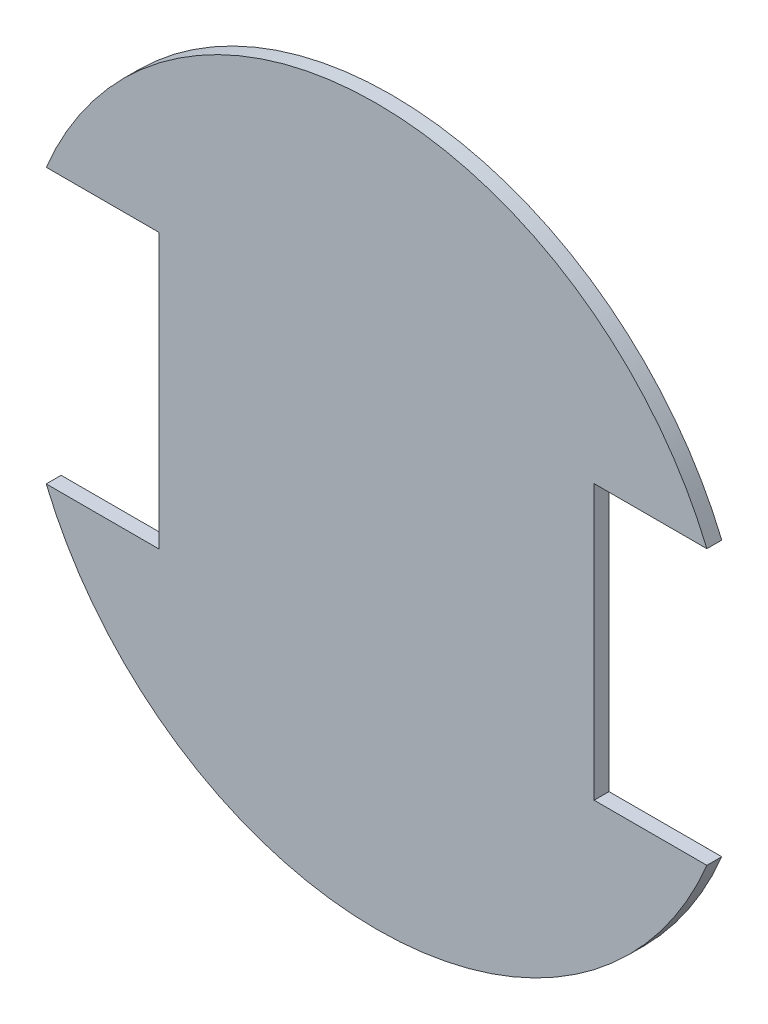
SolidWorks part; units mm, degrees
material "Pine"
ref_plane "Front Plane" through (0, 0, 0) normal (0, 0, 1) x (1, 0, 0)
ref_plane "Top Plane" through (0, 0, 0) normal (0, 1, 0) x (1, 0, 0)
ref_plane "Right Plane" through (0, 0, 0) normal (1, 0, 0) x (0, 0, -1)
sketch "Sketch1" plane through (0, 0, 0) normal (0, 0, 1) x (1, 0, 0)
  line L0 (-1000, 0) -> (49000, 0) construction
  line L1 (0, -1000) -> (0, 49000) construction
  line L2 (73, -46) -> (73, 46)
  line L3 (73, 46) -> (110.8332, 46)
  line L4 (73, -46) -> (110.8332, -46)
  line L5 (-73, -46) -> (-73, 46)
  line L6 (-73, 46) -> (-110.8332, 46)
  line L7 (-73, -46) -> (-110.8332, -46)
  arc A0 (-110.8332, -46) -> (110.8332, -46) centre (0, 0) ccw
  arc A1 (110.8332, 46) -> (-110.8332, 46) centre (0, 0) ccw
  point P10 (73, 0)
  dimension "D1" = 240
  dimension "D2" = 73
  dimension "D3" = 92
extrude "Boss-Extrude1" add sketch "Sketch1" along normal blind 5
sketch "Sketch2" plane through (0, 0, 0) normal (0, 0, -1) x (-1, 0, 0)
  line L0 (0, -1000) -> (0, 49000) construction
  line L1 (-1000, 0) -> (49000, 0) construction
  line L2 (-73, -46) -> (-73, 46) construction
  line L3 (-56, 18.5) -> (-73, 18.5)
  line L4 (-56, 18.5) -> (-56, -18.5)
  line L5 (-56, -18.5) -> (-73, -18.5)
  line L6 (-73, 18.5) -> (-73, -18.5)
  line L7 (-64.5, -18.5) -> (-64.5, 18.5) construction
  line L8 (-56, 0) -> (-73, 0) construction
  line L9 (1000, 0) -> (-49000, 0) construction
  line L10 (64.5, -18.5) -> (64.5, 18.5) construction
  point P4 (-64.5, 0)
  point P11 (64.5, 18.5)
  point P12 (64.5, -18.5)
  point P16 (73, 0)
  point P17 (56, 0)
  point P20 (64.5, 0)
  dimension "D1" = 17
  dimension "D2" = 37
sketch "Sketch3" plane through (0, 0, 5) normal (0, 0, 1) x (1, 0, 0)
  circle A0 centre (0, 0) radius 10
  dimension "D1" = 20
